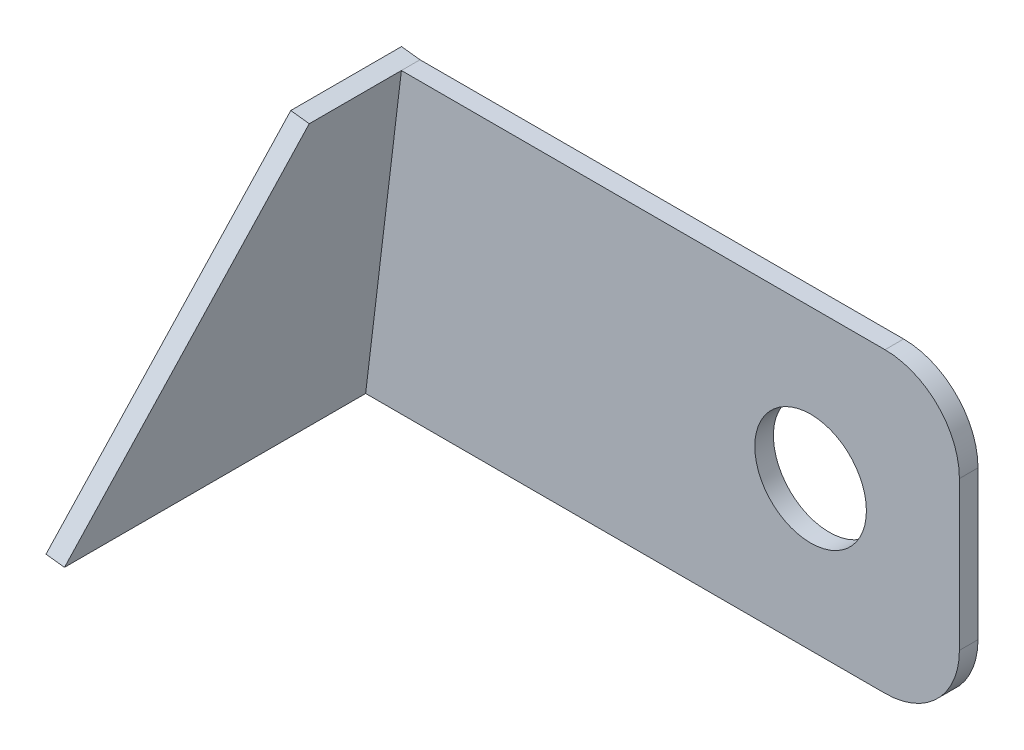
SolidWorks part; units mm, degrees
material "AISI 4130 Steel, annealed at 865C"
ref_plane "Front Plane" through (0, 0, 0) normal (0, 0, 1) x (1, 0, 0)
ref_plane "Top Plane" through (0, 0, 0) normal (0, 1, 0) x (1, 0, 0)
ref_plane "Right Plane" through (0, 0, 0) normal (1, 0, 0) x (0, 0, -1)
sketch "Sketch1" plane through (0, 0, 0) normal (0, 0, 1) x (1, 0, 0)
  line L0 (0, 12.7) -> (-3.0512, -12.7)
  line L1 (0, 12.7) -> (47.625, 12.7)
  line L2 (0, 12.7) -> (0, -12.7) construction
  line L3 (0, -12.7) -> (47.625, -12.7)
  line L4 (47.625, 12.7) -> (47.625, -12.7)
  line L5 (23.8125, -12.7) -> (23.8125, 12.7) construction
  line L6 (0, 0) -> (47.625, 0) construction
  line L7 (-3.0512, -12.7) -> (0, -12.7)
  point P168 (23.8125, 0)
  dimension "D1" = 25.4
  dimension "D2" = 47.625
  dimension "D3" = 83.15
extrude "Boss-Extrude1" add sketch "Sketch1" along normal blind 1.5875
sketch "Sketch3" plane through (0, 0, 1.5875) normal (0, 0, 1) x (1, 0, 0)
  line L0 (0, 0) -> (34.925, 0) construction
  circle A0 centre (34.925, 0) radius 4.7625
  dimension "D1" = 9.525
  dimension "D2" = 34.925
extrude "Cut-Extrude1" cut sketch "Sketch3" against normal through all both and the other way through all contours A0
sketch "Sketch2" plane through (-1.5039, 0.1807, 0) normal (-0.9929, 0.1193, 0) x (0, 0, 1)
  line L5 (0, 12.6093) -> (0, -12.9733)
  line L6 (0, -12.9733) -> (27.2953, -12.9733)
  line L9 (0, 12.6093) -> (9.4538, 12.6093)
  line L10 (9.4538, 12.6093) -> (27.2953, -12.9733)
extrude "Boss-Extrude2" add sketch "Sketch2" along normal blind 1.5875
fillet "Fillet1" radius 6.35
